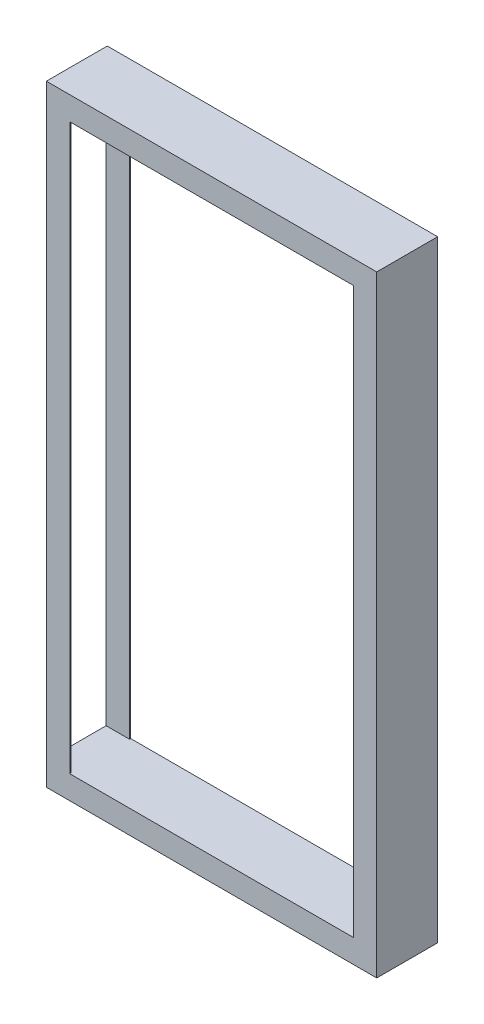
SolidWorks part; units mm, degrees
ref_plane "Front Plane" through (0, 0, 0) normal (1, 0, 0) x (0, 1, 0)
ref_plane "Top Plane" through (0, 0, 0) normal (0, 0, 1) x (0, 1, 0)
ref_plane "Right Plane" through (0, 0, 0) normal (0, 1, 0) x (-1, 0, 0)
sketch "Sketch2" plane through (0, 0, 0) normal (0, 0, 1) x (0, 1, 0)
  line L0 (-130.5, -70.5) -> (-130.5, 70.5)
  line L1 (-120.5, -60.5) -> (120.5, -60.5)
  line L2 (-120.5, -60.5) -> (-120.5, 60.5)
  line L3 (-120.5, 60.5) -> (120.5, 60.5)
  line L4 (120.5, -60.5) -> (120.5, 60.5)
  line L5 (-120.5, -60.5) -> (120.5, 60.5) construction
  line L6 (-120.5, 60.5) -> (120.5, -60.5) construction
  line L7 (-130.5, 70.5) -> (130.5, 70.5)
  line L8 (130.5, -70.5) -> (130.5, 70.5)
  line L9 (-130.5, -70.5) -> (130.5, -70.5)
  point P0 (0, 0)
  dimension "D1" = 121
  dimension "D2" = 241
  dimension "D3" = 10
extrude "Boss-Extrude1" add sketch "Sketch2" along normal blind 26
sketch "Sketch4" plane through (-60.5, 0, 0) normal (1, 0, 0) x (0, 1, 0)
  line L7 (-120.5, 26) -> (-120.5, 0) construction
  line L8 (-120.5, 0.5) -> (120.5, 0.5)
  line L9 (-120.5, 0.5) -> (-120.5, 25.5)
  line L10 (-120.5, 25.5) -> (120.5, 25.5)
  line L11 (120.5, 0.5) -> (120.5, 25.5)
  line L12 (120.5, 26) -> (120.5, 0) construction
  line L13 (120.5, 26) -> (-120.5, 26) construction
  line L14 (120.5, 0) -> (-120.5, 0) construction
  dimension "D1" = 0.5
  dimension "D2" = 0.5
extrude "Cut-Extrude1" cut sketch "Sketch4" against normal through all
